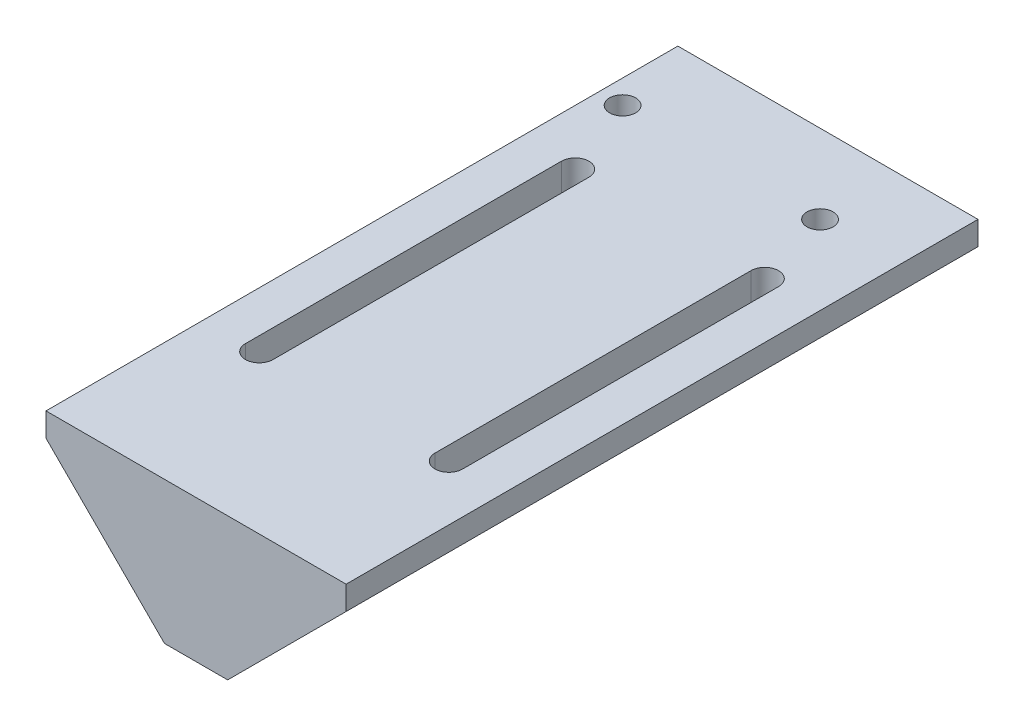
SolidWorks part; units mm, degrees
ref_plane "Front Plane" through (0, 0, 0) normal (0, 0, 1) x (1, 0, 0)
ref_plane "Top Plane" through (0, 0, 0) normal (0, 1, 0) x (1, 0, 0)
ref_plane "Right Plane" through (0, 0, 0) normal (1, 0, 0) x (0, 0, -1)
sketch "Sketch1" plane through (0, 0, 0) normal (0, 0, 1) x (1, 0, 0)
  line L0 (-4, 0) -> (4, 0)
  line L1 (4, 0) -> (19, 15)
  line L2 (19, 15) -> (19, 18)
  line L3 (19, 18) -> (-19, 18)
  line L4 (-19, 18) -> (-19, 15)
  line L5 (-19, 15) -> (-4, 0)
  line L6 (0, 0) -> (0, 11.1187) construction
  point P9 (0, 0)
  dimension "D1" = 8
  dimension "D2" = 15
  dimension "D3" = 135
  dimension "D4" = 135
  dimension "D5" = 3
extrude "Boss-Extrude1" add sketch "Sketch1" along normal blind 80
sketch "Sketch2" plane through (0, 18, 0) normal (0, 1, 0) x (1, 0, 0)
  line L0 (-12, -20) -> (-12, -60) construction
  line L1 (-10.25, -20) -> (-10.25, -60)
  line L2 (-13.75, -20) -> (-13.75, -60)
  line L3 (12, -20) -> (12, -60) construction
  line L4 (13.75, -20) -> (13.75, -60)
  line L5 (10.25, -20) -> (10.25, -60)
  line L6 (0, 0) -> (0, -80) construction
  line L7 (19, -80) -> (-19, -80) construction
  line L8 (-12, -40) -> (12, -40) construction
  arc A0 (-10.25, -20) -> (-13.75, -20) centre (-12, -20) ccw
  arc A1 (-13.75, -60) -> (-10.25, -60) centre (-12, -60) ccw
  arc A2 (13.75, -20) -> (10.25, -20) centre (12, -20) ccw
  arc A3 (10.25, -60) -> (13.75, -60) centre (12, -60) ccw
  point P2 (-12, -40)
  point P8 (12, -40)
  point P21 (0, -40)
  point P22 (0, 0)
  point P23 (-12, -23.0841)
  dimension "D1" = 24
  dimension "D2" = 40
  dimension "D3" = 3.5
extrude "Cut-Extrude1" cut sketch "Sketch2" against normal blind 40
hole_wizard "M4x0.7 Tapped Hole1" positions "Sketch3" profile "Sketch4" tap size "M4x0.7" standard "ANSI Metric" end condition through all
sketch "Sketch3" plane through (0, 18, 0) normal (0, 1, 0) x (1, 0, 0)
  line L0 (19, 0) -> (-19, 0) construction
  point P0 (9.0025, -10)
  point P7 (-15.9975, -10)
  point P10 (0, 0)
  dimension "D1" = 9.0025
  dimension "D2" = 10
  dimension "D3" = 25
sketch "Sketch4" plane through (9.0025, 18, 10) normal (1, 0, 0) x (0, 0, 1)
  line L0 (0, 0) -> (0, 18)
  line L1 (0, 18) -> (1.65, 18)
  line L2 (1.65, 18) -> (1.65, 0)
  line L5 (1.65, 0) -> (0, 0)
  line L11 (0, -6.35) -> (0, 107.95) construction
  dimension "Thru Tap Drill Dia." = 3.3
  dimension "Thru Tap Drill Depth" = 18
cosmetic thread "Hole Thread1" parameters "D2"=4
cosmetic thread "Hole Thread2" parameters "D2"=4
